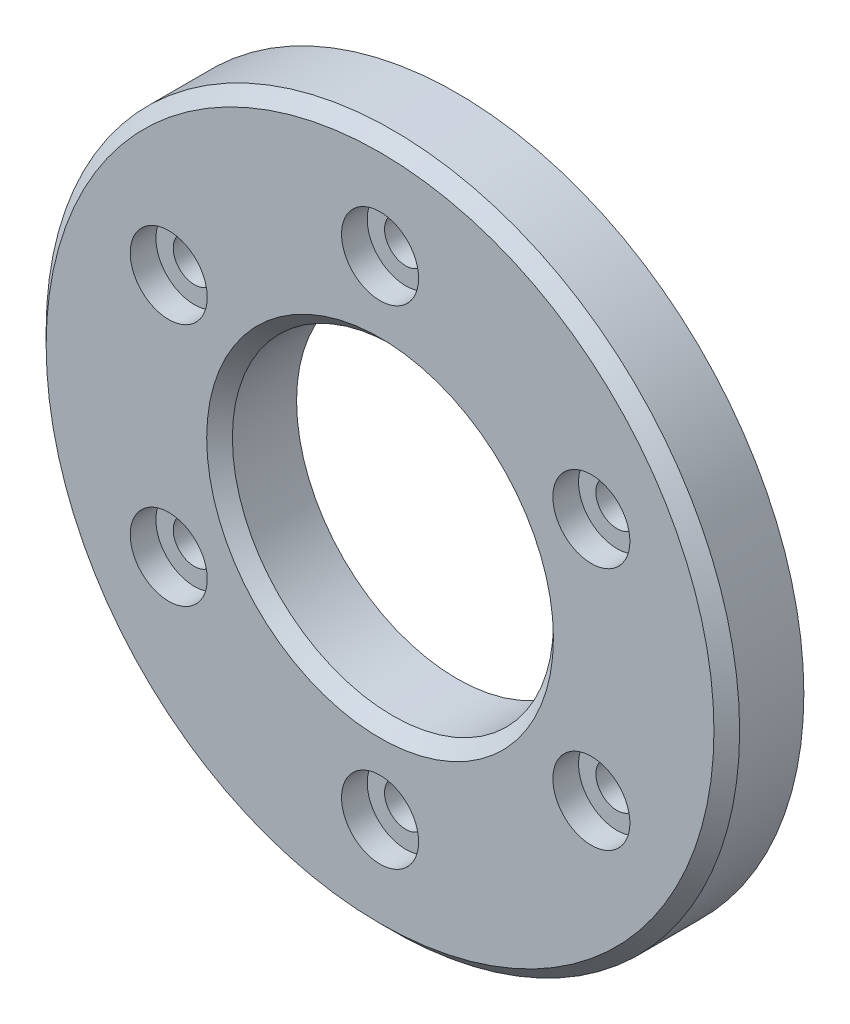
SolidWorks part; units mm, degrees
ref_plane "Front Plane" through (0, 0, 0) normal (0, 0, 1) x (1, 0, 0)
ref_plane "Top Plane" through (0, 0, 0) normal (0, 1, 0) x (1, 0, 0)
ref_plane "Right Plane" through (0, 0, 0) normal (1, 0, 0) x (0, 0, -1)
sketch "Sketch1" plane through (0, 0, 0) normal (0, 0, 1) x (1, 0, 0)
  circle A0 centre (0, 0) radius 27
  circle A1 centre (0, 0) radius 19 construction
  circle A2 centre (0, 19) radius 1.65
  circle A3 centre (16.4545, 9.5) radius 1.65
  circle A4 centre (16.4545, -9.5) radius 1.65
  circle A5 centre (0, -19) radius 1.65
  circle A6 centre (-16.4545, -9.5) radius 1.65
  circle A7 centre (-16.4545, 9.5) radius 1.65
  circle A8 centre (0, 0) radius 12.5
  dimension "D1" = 54
  dimension "D2" = 38
  dimension "D3" = 3.3
  dimension "D5" = 25
  dimension "D4" = 6
extrude "Boss-Extrude1" add sketch "Sketch1" along normal blind 6
sketch "Sketch2" plane through (0, 0, 6) normal (0, 0, 1) x (1, 0, 0)
  circle A0 centre (0, 0) radius 19 construction
  circle A1 centre (0, 19) radius 3
  circle A2 centre (16.4545, 9.5) radius 3
  circle A3 centre (16.4545, -9.5) radius 3
  circle A4 centre (0, -19) radius 3
  circle A5 centre (-16.4545, -9.5) radius 3
  circle A6 centre (-16.4545, 9.5) radius 3
  dimension "D1" = 6
  dimension "D2" = 6
extrude "Cut-Extrude1" cut sketch "Sketch2" against normal blind 2
chamfer "Chamfer1" distance 1 angle 45 2 edges at (12.5, 0, 6) (27, 0, 6)
